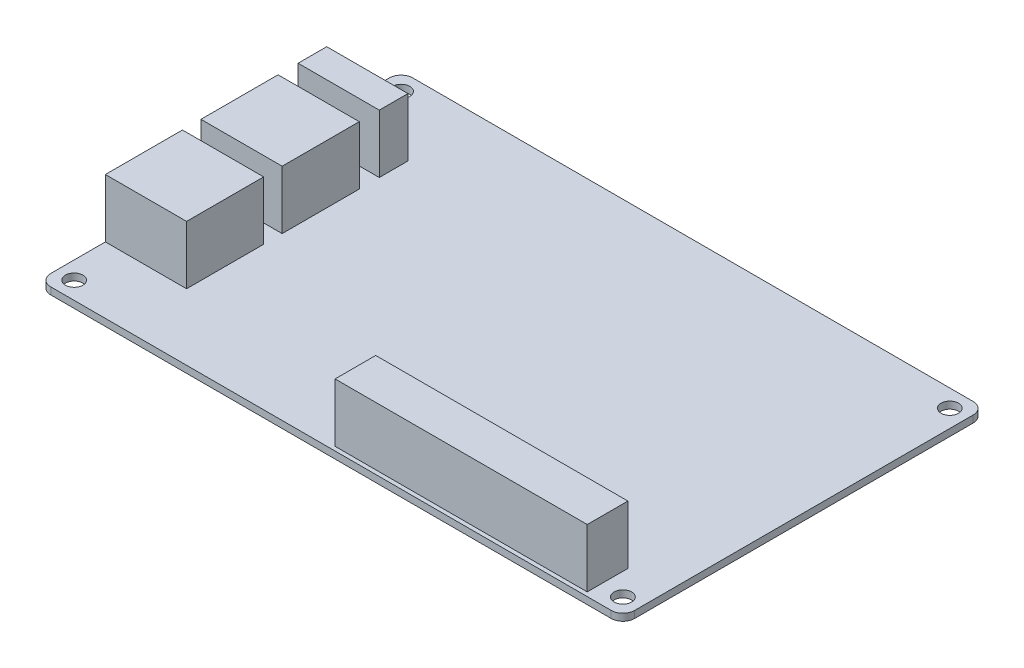
SolidWorks part; units mm, degrees
ref_plane "前视基准面" through (0, 0, 0) normal (0, 0, 1) x (1, 0, 0)
ref_plane "上视基准面" through (0, 0, 0) normal (0, 1, 0) x (1, 0, 0)
ref_plane "右视基准面" through (0, 0, 0) normal (1, 0, 0) x (0, 0, -1)
other "Configuration Table"
sketch "草图1" plane through (0, 0, 0) normal (0, 1, 0) x (1, 0, 0)
  line L0 (-50, 0) -> (50, 0) construction
  line L1 (48, -31) -> (-48, -31)
  line L2 (50, -29) -> (50, 29)
  line L3 (48, 31) -> (-48, 31)
  line L4 (-50, -29) -> (-50, 29)
  line L5 (50, -31) -> (-50, 31) construction
  line L6 (50, 31) -> (-50, -31) construction
  line L7 (0, 31) -> (0, -31) construction
  arc A0 (-48, -31) -> (-50, -29) centre (-48, -29) cw
  arc A1 (48, -31) -> (50, -29) centre (48, -29) ccw
  arc A2 (50, 29) -> (48, 31) centre (48, 29) ccw
  arc A3 (-48, 31) -> (-50, 29) centre (-48, 29) ccw
  circle A4 centre (-47, 28) radius 1.5
  circle A5 centre (47, 28) radius 1.5
  circle A6 centre (47, -28) radius 1.5
  circle A7 centre (-47, -28) radius 1.5
  point P0 (0, 0)
  dimension "D3" = 2
  dimension "D6" = 3
  dimension "D1" = 100
  dimension "D2" = 62
  dimension "D4" = 94
  dimension "D5" = 56
extrude "凸台-拉伸1" add sketch "草图1" along normal blind 1.2
sketch "草图2" plane through (0, 1.2, 0) normal (0, 1, 0) x (1, 0, 0)
  line L0 (-50, 29) -> (-50, -29) construction
  line L1 (-50, -19.6555) -> (-36.0894, -19.6555)
  line L2 (-50, -19.6555) -> (-50, -6.4538)
  line L3 (-50, -6.4538) -> (-36.0894, -6.4538)
  line L4 (-36.0894, -19.6555) -> (-36.0894, -6.4538)
  line L6 (-50, -3.284) -> (-36.0894, -3.284)
  line L7 (-50, -3.284) -> (-50, 9.9258)
  line L8 (-50, 9.9258) -> (-36.0894, 9.9258)
  line L9 (-36.0894, -3.284) -> (-36.0894, 9.9258)
  line L10 (-50, 13.3573) -> (-36.0894, 13.3573)
  line L11 (-50, 13.3573) -> (-50, 18.2633)
  line L12 (-50, 18.2633) -> (-36.0894, 18.2633)
  line L13 (-36.0894, 13.3573) -> (-36.0894, 18.2633)
extrude "凸台-拉伸2" add sketch "草图2" along normal blind 10
sketch "草图3" plane through (0, 1.2, 0) normal (0, 1, 0) x (1, 0, 0)
  line L1 (0, -30.3056) -> (43.1938, -30.3056)
  line L2 (0, -30.3056) -> (0, -23.3434)
  line L3 (0, -23.3434) -> (43.1938, -23.3434)
  line L4 (43.1938, -30.3056) -> (43.1938, -23.3434)
extrude "凸台-拉伸3" add sketch "草图3" along normal blind 10
